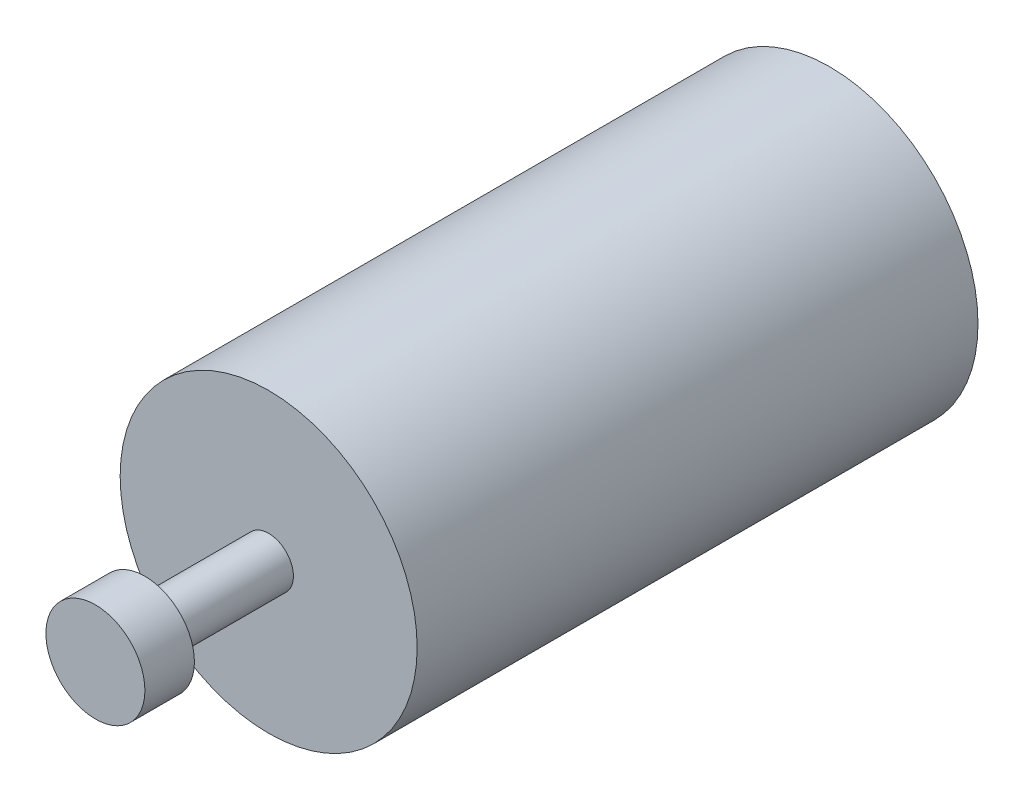
SolidWorks part; units mm, degrees
ref_plane "Front Plane" through (0, 0, 0) normal (0, 0, 1) x (1, 0, 0)
ref_plane "Top Plane" through (0, 0, 0) normal (0, 1, 0) x (1, 0, 0)
ref_plane "Right Plane" through (0, 0, 0) normal (1, 0, 0) x (0, 0, -1)
sketch "Sketch1" plane through (0, 0, 0) normal (0, 0, 1) x (1, 0, 0)
  circle A0 centre (0, 0) radius 3.175
extrude "Boss-Extrude1" add sketch "Sketch1" along normal blind 14.478
sketch "Sketch2" plane through (0, 0, 14.478) normal (0, 0, 1) x (1, 0, 0)
  circle A0 centre (0, 0) radius 38.1
extrude "Boss-Extrude2" add sketch "Sketch2" along normal blind 143.891
sketch "Sketch3" plane through (0, 0, 0) normal (0, 0, -1) x (-1, 0, 0)
  line L1 (-1.27, 5.715) -> (1.27, 5.715)
  line L2 (-1.27, 5.715) -> (-1.27, 0.635)
  line L3 (-1.27, 0.635) -> (1.27, 0.635)
  line L4 (1.27, 5.715) -> (1.27, 0.635)
  line L5 (-1.27, 5.715) -> (1.27, 0.635) construction
  line L6 (-1.27, 0.635) -> (1.27, 5.715) construction
  circle A0 centre (0, 0) radius 3.175 construction
  circle A1 centre (0, 0) radius 3.175 construction
  point P0 (0, 3.175)
extrude "Boss-Extrude3" add sketch "Sketch3" against normal up to surface (14.478 mm away) up to face at (3.175, 0, 14.478)
sketch "Sketch4" plane through (0, 0, 0) normal (0, 0, -1) x (-1, 0, 0)
  circle A0 centre (0, 0) radius 5.9995
extrude "Boss-Extrude4" add sketch "Sketch4" along normal blind 5.08
sketch "Sketch5" plane through (0, 0, 158.369) normal (0, 0, 1) x (1, 0, 0)
  circle A0 centre (0, 0) radius 6.35
extrude "Boss-Extrude5" add sketch "Sketch5" along normal blind 31.75
sketch "Sketch6" plane through (0, 0, 190.119) normal (0, 0, 1) x (1, 0, 0)
  circle A0 centre (0, 0) radius 12.7
extrude "Boss-Extrude6" add sketch "Sketch6" along normal blind 12.7
